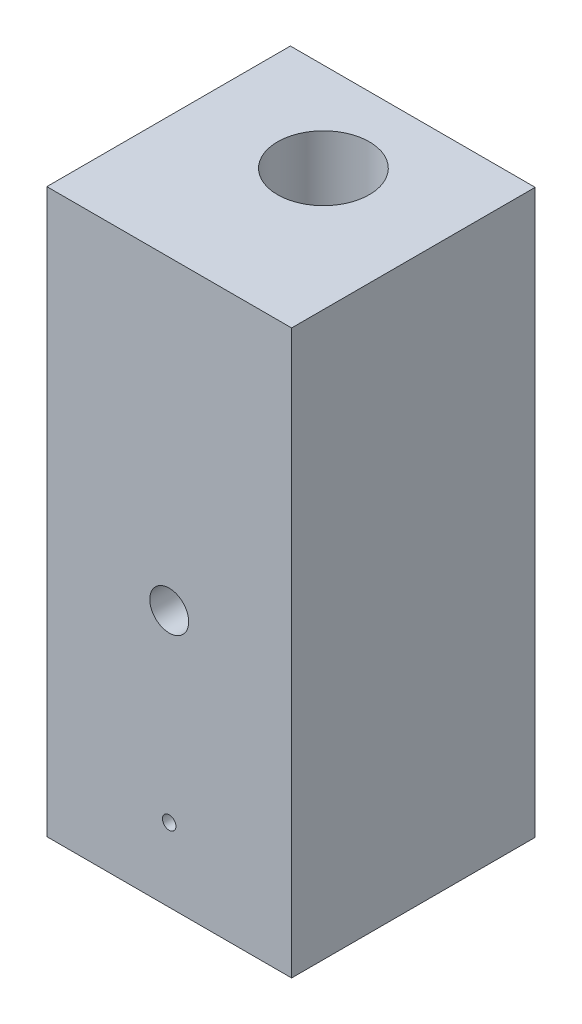
SolidWorks part; units mm, degrees
material "1060 Alloy"
ref_plane "Front Plane" through (0, 0, 0) normal (0, 0, 1) x (1, 0, 0)
ref_plane "Top Plane" through (0, 0, 0) normal (0, 1, 0) x (1, 0, 0)
ref_plane "Right Plane" through (0, 0, 0) normal (1, 0, 0) x (0, 0, -1)
sketch "Sketch1" plane through (0, 0, 0) normal (0, 1, 0) x (1, 0, 0)
  line L1 (-25.4, 25.273) -> (0, 25.273)
  line L2 (-25.4, 25.273) -> (-25.4, 0)
  line L3 (-25.4, 0) -> (0, 0)
  line L4 (0, 25.273) -> (0, 0)
  dimension "D1" = 25.273
  dimension "D2" = 25.4
extrude "Boss-Extrude1" add sketch "Sketch1" along normal blind 58.42
hole_wizard "#54 (0.055) Diameter Hole1" positions "3DSketch1" profile "Sketch2" hole size "#54" standard "ANSI Inch"
sketch3d "3DSketch1"
  line L0 (-25.4, 58.42, 0) -> (0, 58.42, 0) construction
  line L3 (-12.7, 0, 0) -> (-12.7, 58.42, 0) construction
  line L4 (-25.4, 0, 0) -> (0, 0, 0) construction
  line L5 (-12.7, 58.42, 0) -> (-12.7, 58.42, -25.273) construction
  line L6 (0, 58.42, -25.273) -> (-25.4, 58.42, -25.273) construction
  line L8 (0, 58.42, 0) -> (0, 0, 0) construction
  line L9 (-25.4, 58.42, -25.273) -> (-25.4, 58.42, 0) construction
  point P0 (-12.7, 7.62, 0)
  point P24 (-12.7, 26.67, 0)
  point P26 (-12.7, 58.42, -16.002)
  dimension "D1" = 50.8
  dimension "D2" = 12.7
  dimension "D4" = 16.002
  dimension "D3" = 31.75
sketch "Sketch2" plane through (-12.7, 7.62, 0) normal (1, 0, 0) x (0, -1, 0)
  line L0 (0, 0) -> (0, 13.1197)
  line L1 (0, 13.1197) -> (0.6985, 12.7)
  line L2 (0.6985, 12.7) -> (0.6985, 0)
  line L5 (0.6985, 0) -> (0, 0)
  line L10 (0, 13.1197) -> (-0.6985, 12.7) construction
  line L11 (0, -6.35) -> (0, 107.95) construction
  dimension "Hole Dia." = 1.397
  dimension "Hole Depth" = 12.7
  dimension "Drill Angle" = 118
hole_wizard "3/8 (0.375) Diameter Hole2" positions "3DSketch11" profile "Sketch8" hole size "3/8" standard "ANSI Inch"
sketch3d "3DSketch11"
  point P10 (-12.7, 58.42, -16.002)
  point P13 (-12.7, 58.42, -16.002)
  point P16 (-12.7, 58.42, -16.002)
sketch "Sketch8" plane through (-12.7, 58.42, -16.002) normal (1, 0, 0) x (0, 0, 1)
  line L0 (0, 0) -> (0, 53.6616)
  line L1 (0, 53.6616) -> (4.7625, 50.8)
  line L2 (4.7625, 50.8) -> (4.7625, 0)
  line L5 (4.7625, 0) -> (0, 0)
  line L10 (0, 53.6616) -> (-4.7625, 50.8) construction
  line L11 (0, -6.35) -> (0, 107.95) construction
  dimension "Hole Dia." = 9.525
  dimension "Hole Depth" = 50.8
  dimension "Drill Angle" = 118
hole_wizard "#10-32 Tapped Hole1" positions "3DSketch12" profile "Sketch10" tap size "#10-32" standard "ANSI Inch"
sketch3d "3DSketch12"
  point P6 (-12.7, 26.67, 0)
sketch "Sketch10" plane through (-12.7, 26.67, 0) normal (1, 0, 0) x (0, -1, 0)
  line L0 (0, 0) -> (0, 10.16)
  line L1 (0, 10.16) -> (2.0193, 8.9467)
  line L2 (2.0193, 8.9467) -> (2.0193, 0)
  line L5 (2.0193, 0) -> (0, 0)
  line L10 (0, 10.16) -> (-2.0193, 8.9467) construction
  line L11 (0, -6.35) -> (0, 107.95) construction
  dimension "Tap Drill Dia." = 4.0386
  dimension "Tap Drill Depth" = 10.16
  dimension "Drill Angle" = 118
cosmetic thread "Hole Thread1" parameters "D1"=6.35, "D2"=4.826
